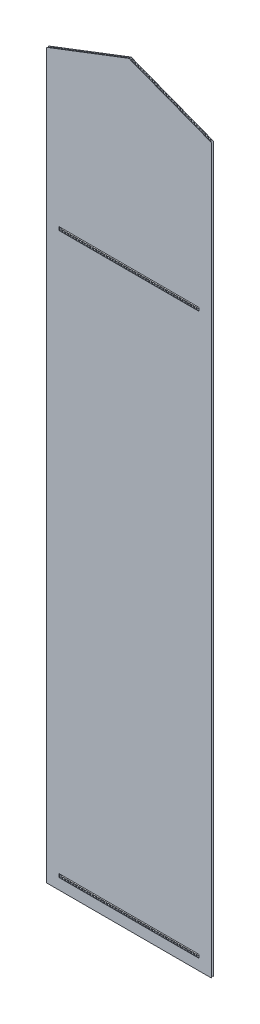
SolidWorks part; units mm, degrees
material "Acrylic (Medium-high impact)"
ref_plane "Front Plane" through (0, 0, 0) normal (0, 0, 1) x (1, 0, 0)
ref_plane "Top Plane" through (0, 0, 0) normal (0, 1, 0) x (1, 0, 0)
ref_plane "Right Plane" through (0, 0, 0) normal (1, 0, 0) x (0, 0, -1)
sketch "Sketch1" plane through (0, 0, 0) normal (0, 1, 0) x (1, 0, 0)
  line L0 (5, -4) -> (-5.3, -4)
  line L1 (-5.3, -4) -> (5, -4) construction
  line L2 (-5, -4) -> (-5, 4) construction
  line L3 (-5.3, 4) -> (5, 4) construction
  line L4 (5, -4) -> (5, 4) construction
  line L5 (-5, -4) -> (5, 4) construction
  line L6 (-5, 4) -> (5, -4) construction
  line L7 (4.7, -3.7) -> (4.7, 3.7)
  line L8 (-5.3, 3.7) -> (4.7, 3.7)
  line L9 (-5.3, -3.7) -> (4.7, -3.7)
  line L10 (5, 4) -> (5, -4)
  line L11 (-5, 4) -> (5, 4) construction
  line L12 (-5, 3.7) -> (5, 3.7) construction
  line L13 (-5, -3.7) -> (5, -3.7) construction
  line L14 (-5, -4) -> (5, -4) construction
  line L15 (5, 4) -> (-5.3, 4)
  line L16 (-5.3, 4) -> (-5.3, -4) construction
  line L17 (-5.3, 4) -> (-5.3, 3.7)
  line L18 (4.7, -4) -> (4.7, 4) construction
  line L19 (-5.3, -3.7) -> (-5.3, -4)
  point P0 (0, 0)
  dimension "D1" = 8
  dimension "D2" = 10
  dimension "D6" = 0.3
  dimension "D3" = 0.3
  dimension "D4" = 0.3
  dimension "D5" = 0.3
extrude "Boss-Extrude1" add sketch "Sketch1" along normal blind 2695.8
pattern_linear "LPattern1" count 59 spacing 10 along (1, 0, 0) of "Boss-Extrude1"
sketch "Sketch2" plane through (0, 0, 4) normal (0, 0, 1) x (1, 0, 0)
  line L0 (585, 45) -> (-5.3, 45) construction
  line L2 (-5.3, 2695.8) -> (-5.3, 0) construction
  line L3 (-5.3, 0) -> (585, 0) construction
  line L4 (585, 51) -> (-5.3, 51) construction
  line L5 (585, 38.9) -> (-5.3, 38.9) construction
  line L6 (289.85, 38.9) -> (289.85, 51) construction
  line L7 (539.95, 38.9) -> (539.95, 51)
  line L8 (39.75, 38.9) -> (39.75, 51)
  line L9 (39.75, 51) -> (539.95, 51)
  line L10 (539.95, 38.9) -> (39.75, 38.9)
  line L11 (585, 45) -> (-5.3, 45) construction
  line L13 (585, 51) -> (-5.3, 51) construction
  line L14 (-5.3, 2695.8) -> (585, 2695.8) construction
  line L17 (583, 2695.8) -> (-5.3, 2695.8) construction
  line L18 (585, 0) -> (583, 0)
  line L19 (288.85, 2695.8) -> (-5.3, 2582.8864)
  line L22 (585, 2695.8) -> (585, 0) construction
  line L23 (-5.3, 2705.6473) -> (585.0153, 2705.6473)
  line L25 (583, 0) -> (583, 2582.8864)
  line L26 (-5.3, 2582.8864) -> (583, 2582.8864) construction
  line L27 (288.85, 2582.8864) -> (288.85, 2695.8) construction
  line L28 (288.85, 2695.8) -> (583, 2582.8864)
  line L29 (-5.3, 2582.8864) -> (-5.3, 2695.8)
  line L30 (-5.3, 2695.8) -> (583, 2695.8) construction
  line L31 (585, 2695.8) -> (585.0153, 2705.6473)
  line L32 (585, 0) -> (585, 2695.8)
  line L33 (-5.3, 2695.8) -> (-5.3, 2705.6473)
  dimension "D1" = 45
  dimension "D6" = 2
  dimension "D7" = 69
  dimension "D8" = 9.8473
  dimension "D2" = 6
  dimension "D3" = 12.1
  dimension "D4" = 250.1
  dimension "D5" = 250.1
extrude "Cut-Extrude1" cut sketch "Sketch2" against normal through all
pattern_linear "LPattern2" count 2 spacing 2000 along (0, 1, 0) of "Cut-Extrude1"
